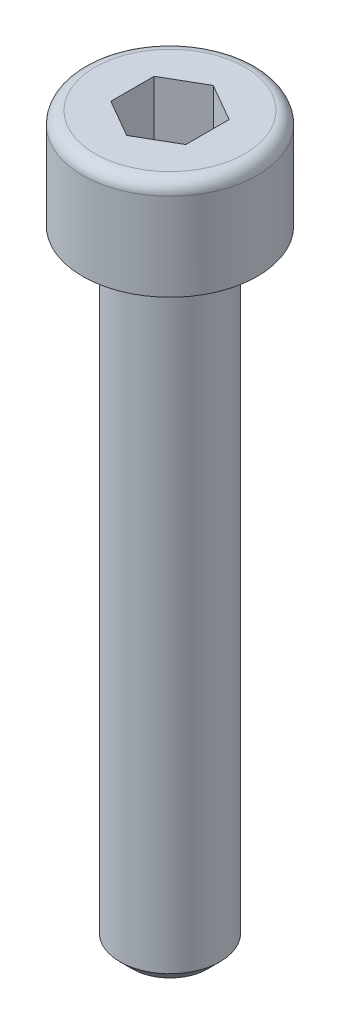
SolidWorks part; units mm, degrees
material "acero"
ref_plane "Alzado" through (0, 0, 0) normal (0, 0, 1) x (1, 0, 0)
ref_plane "Planta" through (0, 0, 0) normal (0, 1, 0) x (1, 0, 0)
ref_plane "Vista lateral" through (0, 0, 0) normal (1, 0, 0) x (0, 0, -1)
sketch "Croquis1" plane through (0, 0, 0) normal (0, 0, 1) x (1, 0, 0)
  line L0 (0, 0) -> (0, -60.9498) construction
  line L1 (0, 0) -> (3.5, 0)
  line L2 (3.5, 0) -> (3.5, -4)
  line L3 (3.5, -4) -> (2, -4)
  line L4 (2, -4) -> (2, -29)
  line L5 (2, -29) -> (0, -29)
  line L6 (0, -29) -> (0, 0)
  dimension "D1" = 25
  dimension "D2" = 4
  dimension "D3" = 7
  dimension "D4" = 4
revolve "Revolución1" add sketch "Croquis1" angle 360 about L0
sketch "Croquis2" plane through (0, 0, 0) normal (0, 1, 0) x (1, 0, 0)
  line L1 (1.5, 0.866) -> (0, 1.7321)
  line L2 (0, 1.7321) -> (-1.5, 0.866)
  line L3 (-1.5, 0.866) -> (-1.5, -0.866)
  line L4 (-1.5, -0.866) -> (0, -1.7321)
  line L5 (0, -1.7321) -> (1.5, -0.866)
  line L6 (1.5, -0.866) -> (1.5, 0.866)
  circle A0 centre (0, 0) radius 1.5 construction
  dimension "D1" = 3
extrude "Cortar-Extruir1" cut sketch "Croquis2" against normal blind 3
chamfer "Chaflán1" distance 0.5 angle 45 1 edges at (0, -29, 2)
fillet "Redondeo1" radius 0.5 1 edges at (0, 0, 3.5)
